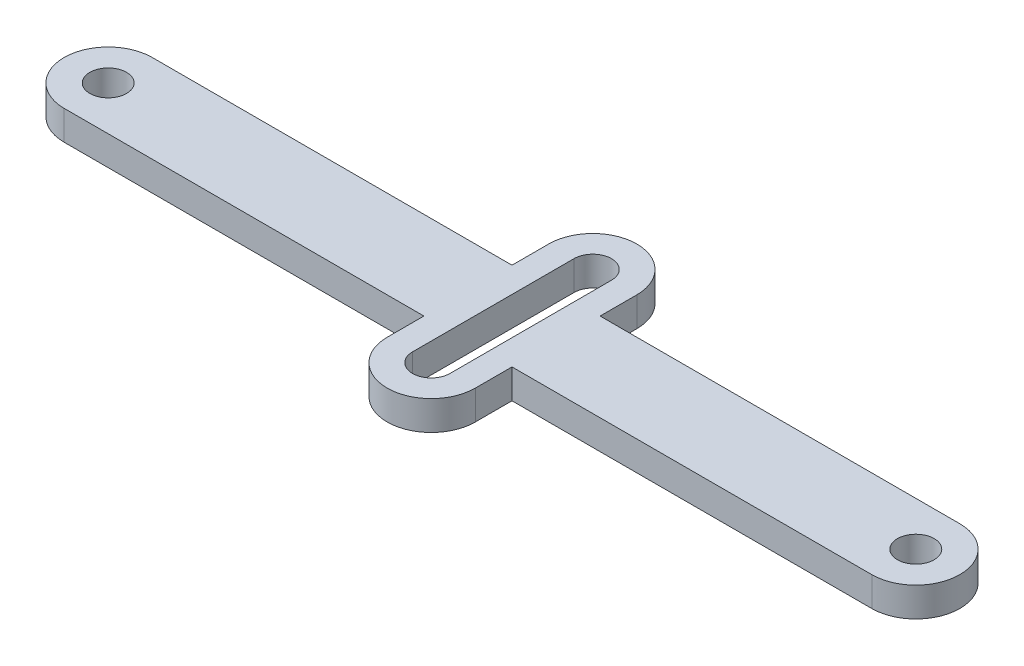
SolidWorks part; units mm, degrees
ref_plane "前视基准面" through (0, 0, 0) normal (0, 0, 1) x (1, 0, 0)
ref_plane "上视基准面" through (0, 0, 0) normal (0, 1, 0) x (1, 0, 0)
ref_plane "右视基准面" through (0, 0, 0) normal (1, 0, 0) x (0, 0, -1)
sketch "草图1" plane through (0, 0, 0) normal (0, 1, 0) x (1, 0, 0)
  line L0 (-55, 0) -> (55, 0) construction
  line L1 (-55, 6) -> (55, 6)
  line L2 (-55, -6) -> (55, -6)
  arc A0 (55, -6) -> (55, 6) centre (55, 0) ccw
  arc A1 (-55, 6) -> (-55, -6) centre (-55, 0) ccw
  circle A2 centre (55, 0) radius 2.5
  circle A3 centre (-55, 0) radius 2.5
  point P4 (0, 0)
  dimension "D2" = 12
  dimension "D3" = 5
  dimension "D1" = 110
extrude "凸台-拉伸1" add sketch "草图1" along normal blind 4
sketch "草图2" plane through (0, 4, 0) normal (0, 1, 0) x (1, 0, 0)
  line L0 (0, -11) -> (0, 11) construction
  line L1 (-6, -11) -> (-6, 11)
  line L2 (6, -11) -> (6, 11)
  arc A0 (-6, -11) -> (6, -11) centre (0, -11) ccw
  arc A1 (6, 11) -> (-6, 11) centre (0, 11) ccw
  point P2 (0, 0)
  dimension "D2" = 6
  dimension "D1" = 22
extrude "凸台-拉伸2" add sketch "草图2" against normal up to surface (4 mm away) up to face at (0, 0, 0)
sketch "草图3" plane through (0, 4, 0) normal (0, 1, 0) x (1, 0, 0)
  line L2 (0, -11) -> (0, 11) construction
  line L3 (-2.55, -11) -> (-2.55, 11)
  line L4 (2.55, -11) -> (2.55, 11)
  arc A5 (-2.55, -11) -> (2.55, -11) centre (0, -11) ccw
  arc A7 (2.55, 11) -> (-2.55, 11) centre (0, 11) ccw
  point P2 (0, 0)
  dimension "D1" = 2.55
extrude "切除-拉伸1" cut sketch "草图3" against normal blind 5
